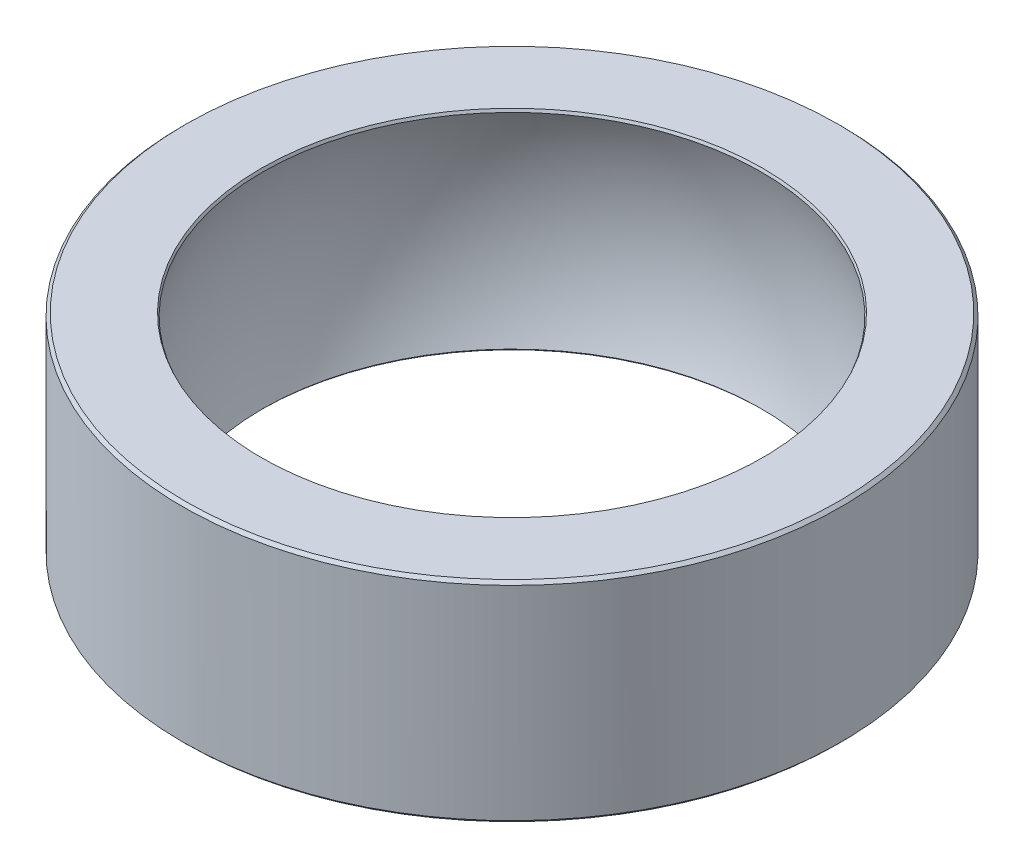
SolidWorks part; units mm, degrees
material "AISI 4340 Steel, annealed"
ref_plane "Front Plane" through (0, 0, 0) normal (0, 0, 1) x (1, 0, 0)
ref_plane "Top Plane" through (0, 0, 0) normal (0, 1, 0) x (1, 0, 0)
ref_plane "Right Plane" through (0, 0, 0) normal (1, 0, 0) x (0, 0, -1)
sketch "Sketch2" plane through (0, 0, 0) normal (0, 0, 1) x (1, 0, 0)
  line L0 (0, 0) -> (0, 3.5) construction
  line L1 (-11, -3.5) -> (-11, 3.5)
  line L2 (-11, 3.5) -> (-8.2916, 3.5)
  line L3 (-11, 0) -> (-9, 0) construction
  line L4 (-11, -3.5) -> (-8.2916, -3.5)
  arc A0 (-8.2916, 3.5) -> (-8.2916, -3.5) centre (0, 0) ccw
  dimension "D1" = 11
  dimension "D2" = 9
  dimension "D3" = 3.5
revolve "Revolve1" add sketch "Sketch2" angle 360 about L0
chamfer "Chamfer1" distance 0.1 angle 45 4 edges at (0, -3.5, -8.2916) (0, 3.5, -8.2916) (0, 3.5, -11) (0, -3.5, -11)
